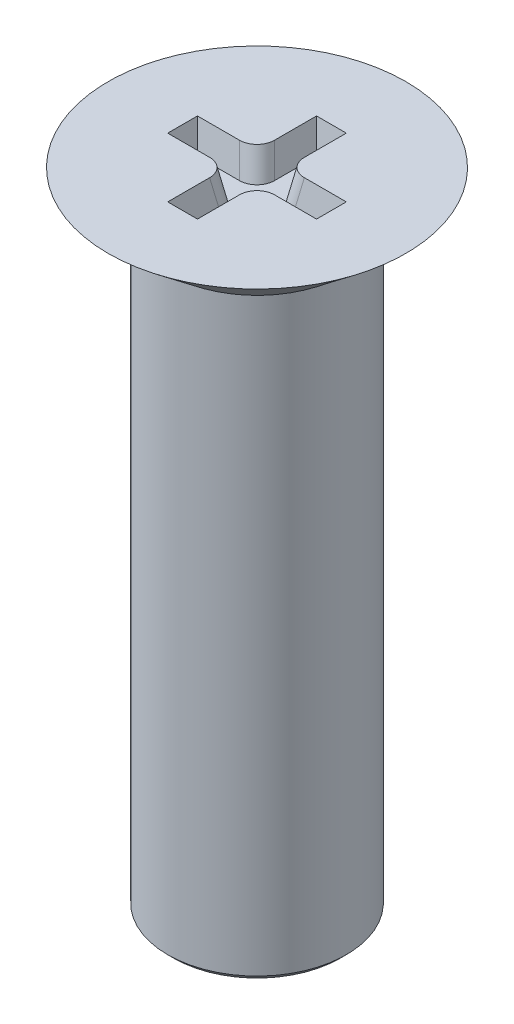
SolidWorks part; units mm, degrees
material "AISI 321 退火不锈钢 (SS)"
ref_plane "前视基准面" through (0, 0, 0) normal (0, 0, 1) x (1, 0, 0)
ref_plane "上视基准面" through (0, 0, 0) normal (0, 1, 0) x (1, 0, 0)
ref_plane "右视基准面" through (0, 0, 0) normal (1, 0, 0) x (0, 0, -1)
other "Configuration Table"
sketch "草图1" plane through (0, 0, 0) normal (0, 0, 1) x (1, 0, 0)
  line L0 (0, 0) -> (2.5, 0)
  line L1 (2.5, 0) -> (1.5, -0.8)
  line L2 (1.5, -0.8) -> (0, -0.8)
  line L3 (0, -0.8) -> (0, 0)
  dimension "D1" = 2.5
  dimension "D2" = 0.8
  dimension "D3" = 1.5
revolve "旋转1" add sketch "草图1" angle 360 about L3
sketch "草图2" plane through (0, -0.8, 0) normal (0, -1, 0) x (1, 0, 0)
  circle A1 centre (0, 0) radius 1.5
  circle A2 centre (0, 0) radius 1.5
  dimension "D1" = 0
extrude "凸台-拉伸1" add sketch "草图2" along normal blind 10
cosmetic thread "装饰螺纹线1" parameters "D2"=2.459
chamfer "倒角1" distance 0.1 angle 45 1 edges at (0, -10.8, -1.5)
sketch "草图3" plane through (0, 0, 0) normal (0, 1, 0) x (1, 0, 0)
  line L1 (-1.25, -0.25) -> (1.25, -0.25)
  line L2 (-1.25, -0.25) -> (-1.25, 0.25)
  line L3 (-1.25, 0.25) -> (1.25, 0.25)
  line L4 (1.25, -0.25) -> (1.25, 0.25)
  line L5 (-1.25, -0.25) -> (1.25, 0.25) construction
  line L6 (-1.25, 0.25) -> (1.25, -0.25) construction
  line L7 (-0.25, 1.25) -> (0.25, 1.25)
  line L8 (-0.25, 1.25) -> (-0.25, -1.25)
  line L9 (-0.25, -1.25) -> (0.25, -1.25)
  line L10 (0.25, 1.25) -> (0.25, -1.25)
  line L11 (-0.25, 1.25) -> (0.25, -1.25) construction
  line L12 (-0.25, -1.25) -> (0.25, 1.25) construction
  point P0 (0, 0)
  point P6 (0, 0)
  dimension "D1" = 0.5
  dimension "D2" = 0.5
  dimension "D3" = 2.5
  dimension "D4" = 2.5
extrude "切除-拉伸1" cut sketch "草图3" against normal blind 0.5 draft 10 contours L3 L10 L1 L4 | L10 L7 L8 L3 | L8 L3 L2 L1 | L10 L3 L8 L1 | L10 L1 L8 L9
fillet "圆角1" radius 0.3 4 edges at (-0.2059, -0.25, -0.2059) (0.2059, -0.25, -0.2059) (-0.2059, -0.25, 0.2059) (0.2059, -0.25, 0.2059)
